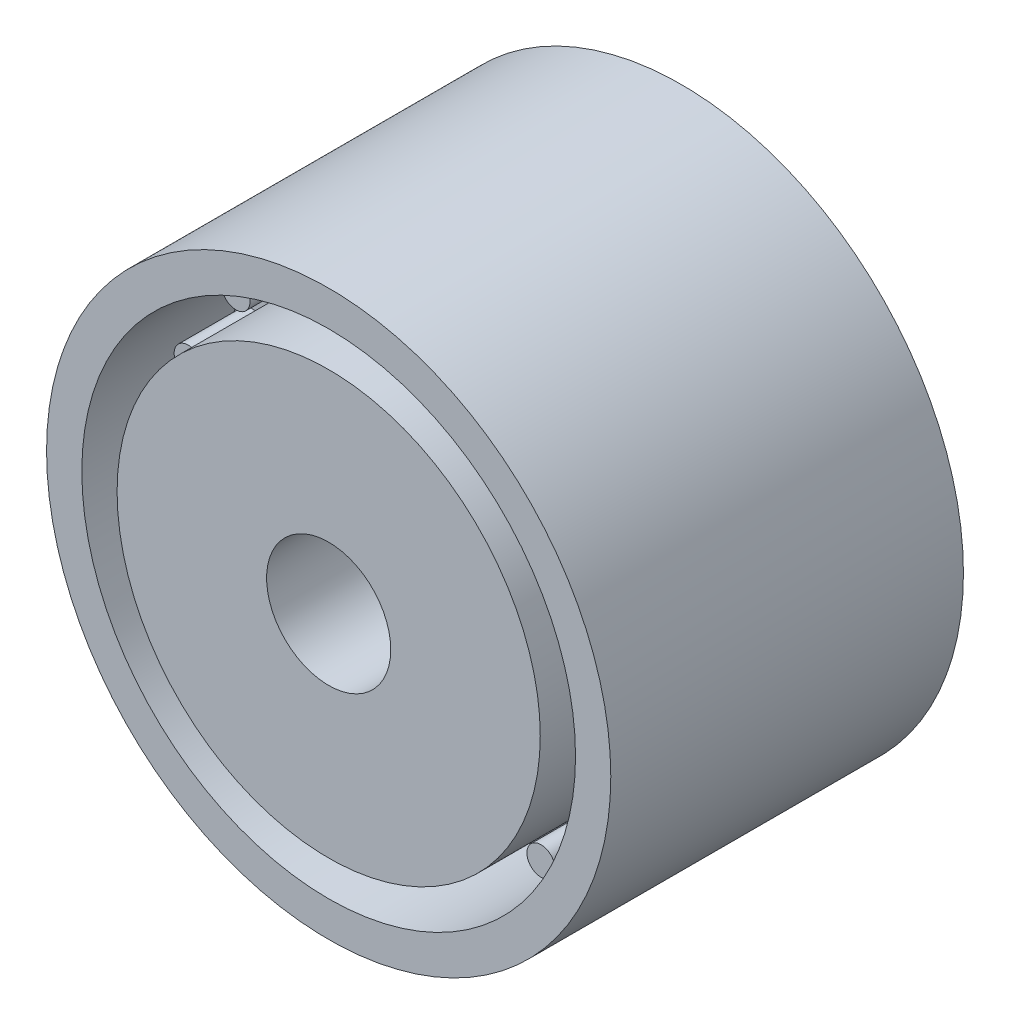
SolidWorks part; units mm, degrees
ref_plane "Ön Düzlem" through (0, 0, 0) normal (0, 0, 1) x (1, 0, 0)
ref_plane "Üst Düzlem" through (0, 0, 0) normal (0, 1, 0) x (1, 0, 0)
ref_plane "Sağ Düzlem" through (0, 0, 0) normal (1, 0, 0) x (0, 0, -1)
sketch "Sketch1" plane through (0, 0, 0) normal (0, 0, 1) x (1, 0, 0)
  circle A0 centre (0, 0) radius 20
  dimension "D1" = 40
extrude "Boss-Extrude1" add sketch "Sketch1" against normal blind 25
sketch "Sketch2" plane through (0, 0, 0) normal (0, 0, 1) x (1, 0, 0)
  circle A0 centre (0, 0) radius 17.5
  circle A1 centre (0, 0) radius 15
  dimension "D1" = 30
  dimension "D2" = 35
extrude "Cut-Extrude1" cut sketch "Sketch2" against normal blind 10
sketch "Sketch3" plane through (0, 0, 0) normal (0, 0, 1) x (1, 0, 0)
  circle A0 centre (0, 0) radius 4.4
  dimension "D1" = 8.8
extrude "Cut-Extrude2" cut sketch "Sketch3" against normal blind 7
sketch "Sketch4" plane through (0, 0, -25) normal (0, 0, -1) x (-1, 0, 0)
  circle A0 centre (0, 0) radius 12.5
  dimension "D1" = 25
extrude "Cut-Extrude3" cut sketch "Sketch4" against normal blind 5
sketch "Sketch5" plane through (0, 0, -10) normal (0, 0, 1) x (1, 0, 0)
  line L0 (0, -20) -> (0, 20) construction
  line L1 (-20, 0) -> (20, 0) construction
  circle A0 centre (0, 0) radius 20 construction
  circle A1 centre (0, 0) radius 16.25 construction
  circle A2 centre (0, 16.25) radius 1
  circle A3 centre (0, 0) radius 16.25 construction
  circle A4 centre (6.6095, 14.8451) radius 1
  circle A5 centre (0, 0) radius 16.25 construction
  circle A6 centre (12.0761, 10.8734) radius 1
  circle A7 centre (0, 0) radius 16.25 construction
  circle A8 centre (15.4547, 5.0215) radius 1
  circle A9 centre (0, 0) radius 16.25 construction
  circle A10 centre (16.161, -1.6986) radius 1
  circle A11 centre (0, 0) radius 16.25 construction
  circle A12 centre (14.0729, -8.125) radius 1
  circle A13 centre (0, 0) radius 16.25 construction
  circle A14 centre (9.5515, -13.1465) radius 1
  circle A15 centre (0, 0) radius 16.25 construction
  circle A16 centre (3.3786, -15.8949) radius 1
  circle A17 centre (0, 0) radius 16.25 construction
  circle A18 centre (-3.3786, -15.8949) radius 1
  circle A19 centre (0, 0) radius 16.25 construction
  circle A20 centre (-9.5515, -13.1465) radius 1
  circle A21 centre (0, 0) radius 16.25 construction
  circle A22 centre (-14.0729, -8.125) radius 1
  circle A23 centre (0, 0) radius 16.25 construction
  circle A24 centre (-16.161, -1.6986) radius 1
  circle A25 centre (0, 0) radius 16.25 construction
  circle A26 centre (-15.4547, 5.0215) radius 1
  circle A27 centre (0, 0) radius 16.25 construction
  circle A28 centre (-12.0761, 10.8734) radius 1
  circle A29 centre (0, 0) radius 16.25 construction
  circle A30 centre (-6.6095, 14.8451) radius 1
  dimension "D1" = 32.5
  dimension "D2" = 2
  dimension "D3" = 15
extrude "Boss-Extrude2" add sketch "Sketch5" along normal blind 4.5
